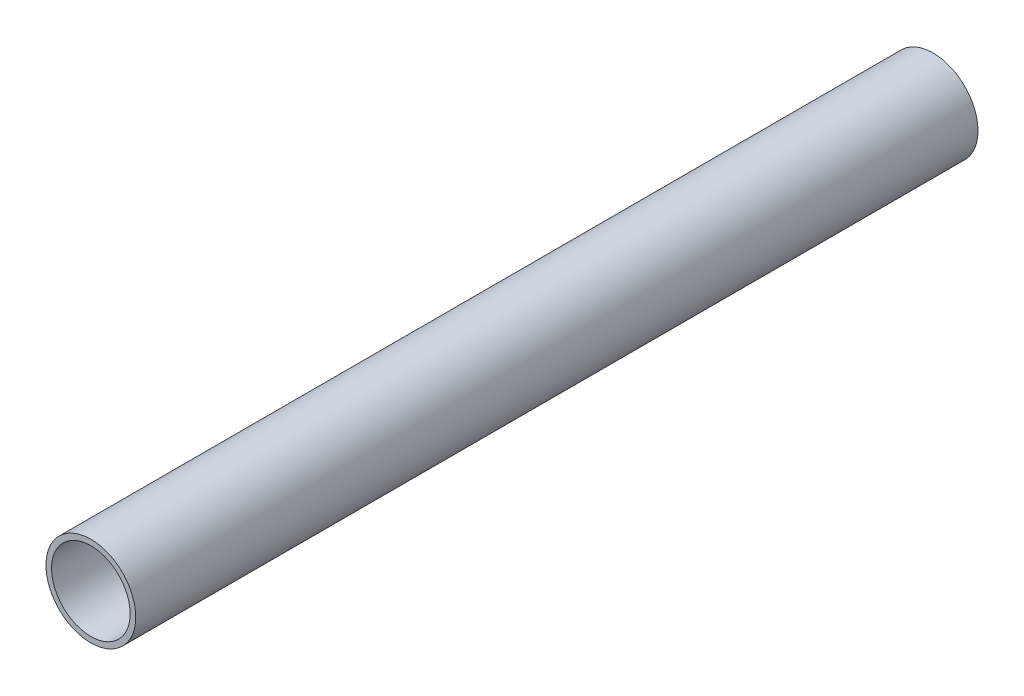
SolidWorks part; units mm, degrees
ref_plane "前视基准面" through (0, 0, 0) normal (0, 0, 1) x (1, 0, 0)
ref_plane "上视基准面" through (0, 0, 0) normal (0, 1, 0) x (1, 0, 0)
ref_plane "右视基准面" through (0, 0, 0) normal (1, 0, 0) x (0, 0, -1)
sketch "草图1" plane through (0, 0, 0) normal (0, 0, 1) x (1, 0, 0)
  circle A0 centre (0, 0) radius 7
  circle A1 centre (0, 0) radius 8
extrude "凸台-拉伸1" add sketch "草图1" along normal blind 150
